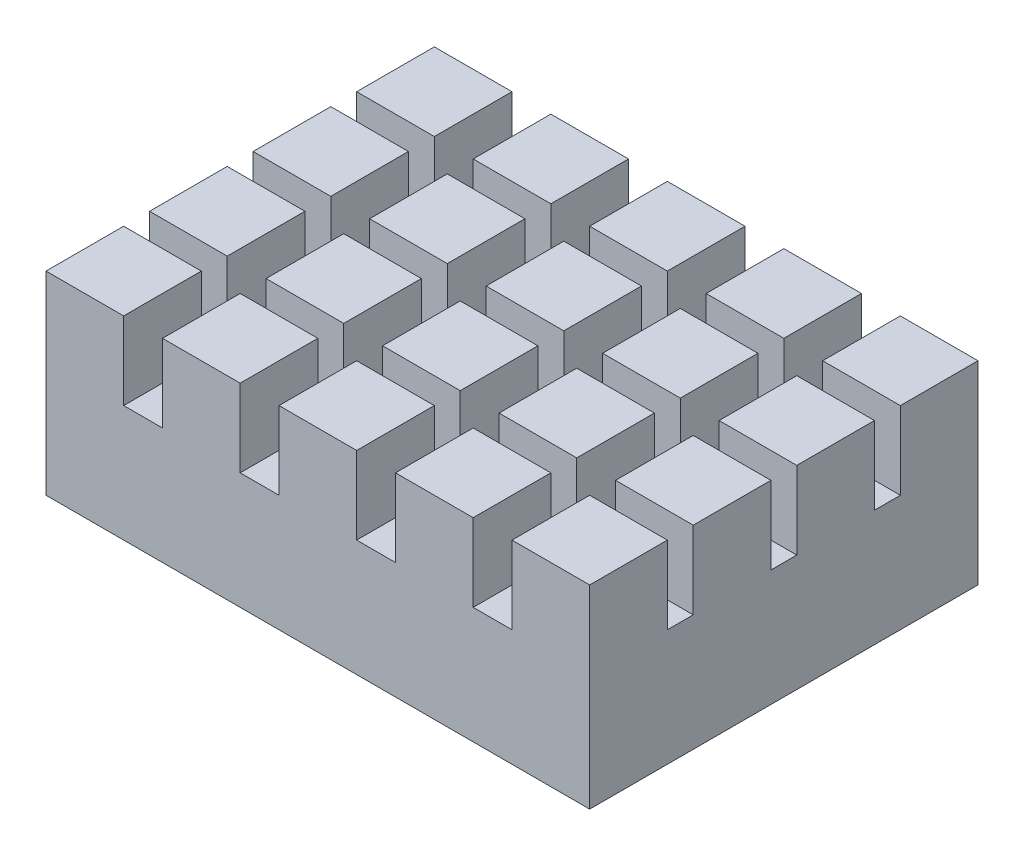
SolidWorks part; units mm, degrees
ref_plane "Front Plane" through (0, 0, 0) normal (0, 0, 1) x (1, 0, 0)
ref_plane "Top Plane" through (0, 0, 0) normal (0, 1, 0) x (1, 0, 0)
ref_plane "Right Plane" through (0, 0, 0) normal (1, 0, 0) x (0, 0, -1)
sketch "Sketch1" plane through (0, 0, 0) normal (0, 1, 0) x (1, 0, 0)
  line L1 (0, 0) -> (14, 0)
  line L2 (0, 0) -> (0, 10)
  line L3 (0, 10) -> (14, 10)
  line L4 (14, 0) -> (14, 10)
  dimension "D1" = 14
  dimension "D2" = 10
extrude "Boss-Extrude1" add sketch "Sketch1" along normal blind 3
sketch "Sketch2" plane through (0, 3, 0) normal (0, 1, 0) x (1, 0, 0)
  line L0 (3, 0) -> (3, 2)
  line L1 (0, 0) -> (2, 0)
  line L2 (0, 0) -> (0, 2)
  line L3 (0, 2) -> (2, 2)
  line L4 (2, 0) -> (2, 2)
  line L5 (3, 2) -> (5, 2)
  line L6 (5, 0) -> (5, 2)
  line L7 (3, 0) -> (5, 0)
  line L8 (6, 0) -> (6, 2)
  line L9 (6, 2) -> (8, 2)
  line L10 (8, 0) -> (8, 2)
  line L11 (6, 0) -> (8, 0)
  line L12 (9, 0) -> (9, 2)
  line L13 (9, 2) -> (11, 2)
  line L14 (11, 0) -> (11, 2)
  line L15 (9, 0) -> (11, 0)
  line L28 (3, 2.6667) -> (3, 4.6667)
  line L29 (3, 4.6667) -> (5, 4.6667)
  line L30 (5, 2.6667) -> (5, 4.6667)
  line L31 (3, 2.6667) -> (5, 2.6667)
  line L32 (6, 2.6667) -> (6, 4.6667)
  line L33 (6, 4.6667) -> (8, 4.6667)
  line L34 (8, 2.6667) -> (8, 4.6667)
  line L35 (6, 2.6667) -> (8, 2.6667)
  line L36 (9, 2.6667) -> (9, 4.6667)
  line L37 (9, 4.6667) -> (11, 4.6667)
  line L38 (11, 2.6667) -> (11, 4.6667)
  line L39 (9, 2.6667) -> (11, 2.6667)
  line L52 (3, 5.3333) -> (3, 7.3333)
  line L53 (3, 7.3333) -> (5, 7.3333)
  line L54 (5, 5.3333) -> (5, 7.3333)
  line L55 (3, 5.3333) -> (5, 5.3333)
  line L56 (6, 5.3333) -> (6, 7.3333)
  line L57 (6, 7.3333) -> (8, 7.3333)
  line L58 (8, 5.3333) -> (8, 7.3333)
  line L59 (6, 5.3333) -> (8, 5.3333)
  line L60 (9, 5.3333) -> (9, 7.3333)
  line L61 (9, 7.3333) -> (11, 7.3333)
  line L62 (11, 5.3333) -> (11, 7.3333)
  line L63 (9, 5.3333) -> (11, 5.3333)
  line L76 (3, 8) -> (3, 10)
  line L77 (3, 10) -> (5, 10)
  line L78 (5, 8) -> (5, 10)
  line L79 (3, 8) -> (5, 8)
  line L80 (6, 8) -> (6, 10)
  line L81 (6, 10) -> (8, 10)
  line L82 (8, 8) -> (8, 10)
  line L83 (6, 8) -> (8, 8)
  line L84 (9, 8) -> (9, 10)
  line L85 (9, 10) -> (11, 10)
  line L86 (11, 8) -> (11, 10)
  line L87 (9, 8) -> (11, 8)
  line L100 (0, 2.6667) -> (0, 4.6667)
  line L101 (0, 4.6667) -> (2, 4.6667)
  line L102 (2, 2.6667) -> (2, 4.6667)
  line L103 (0, 2.6667) -> (2, 2.6667)
  line L104 (0, 5.3333) -> (0, 7.3333)
  line L105 (0, 7.3333) -> (2, 7.3333)
  line L106 (2, 5.3333) -> (2, 7.3333)
  line L107 (0, 5.3333) -> (2, 5.3333)
  line L108 (0, 8) -> (0, 10)
  line L109 (0, 10) -> (2, 10)
  line L110 (2, 8) -> (2, 10)
  line L111 (0, 8) -> (2, 8)
  line L112 (0, 0) -> (14, 0) construction
  line L113 (12, 0) -> (12, 2)
  line L114 (12, 2) -> (14, 2)
  line L115 (14, 0) -> (14, 2)
  line L116 (12, 0) -> (14, 0)
  line L117 (12, 2.6667) -> (12, 4.6667)
  line L118 (12, 4.6667) -> (14, 4.6667)
  line L119 (14, 2.6667) -> (14, 4.6667)
  line L120 (12, 2.6667) -> (14, 2.6667)
  line L121 (12, 5.3333) -> (12, 7.3333)
  line L122 (12, 7.3333) -> (14, 7.3333)
  line L123 (14, 5.3333) -> (14, 7.3333)
  line L124 (12, 5.3333) -> (14, 5.3333)
  line L125 (12, 8) -> (12, 10)
  line L126 (12, 10) -> (14, 10)
  line L127 (14, 8) -> (14, 10)
  line L128 (12, 8) -> (14, 8)
  point P5 (0, 0)
  point P6 (0, 0)
  point P7 (9.287, 0)
  point P48 (14, 10)
  dimension "D1" = 2
  dimension "D2" = 2
  dimension "D3" = 5
  dimension "D4" = 4
extrude "Boss-Extrude2" add sketch "Sketch2" along normal blind 2
